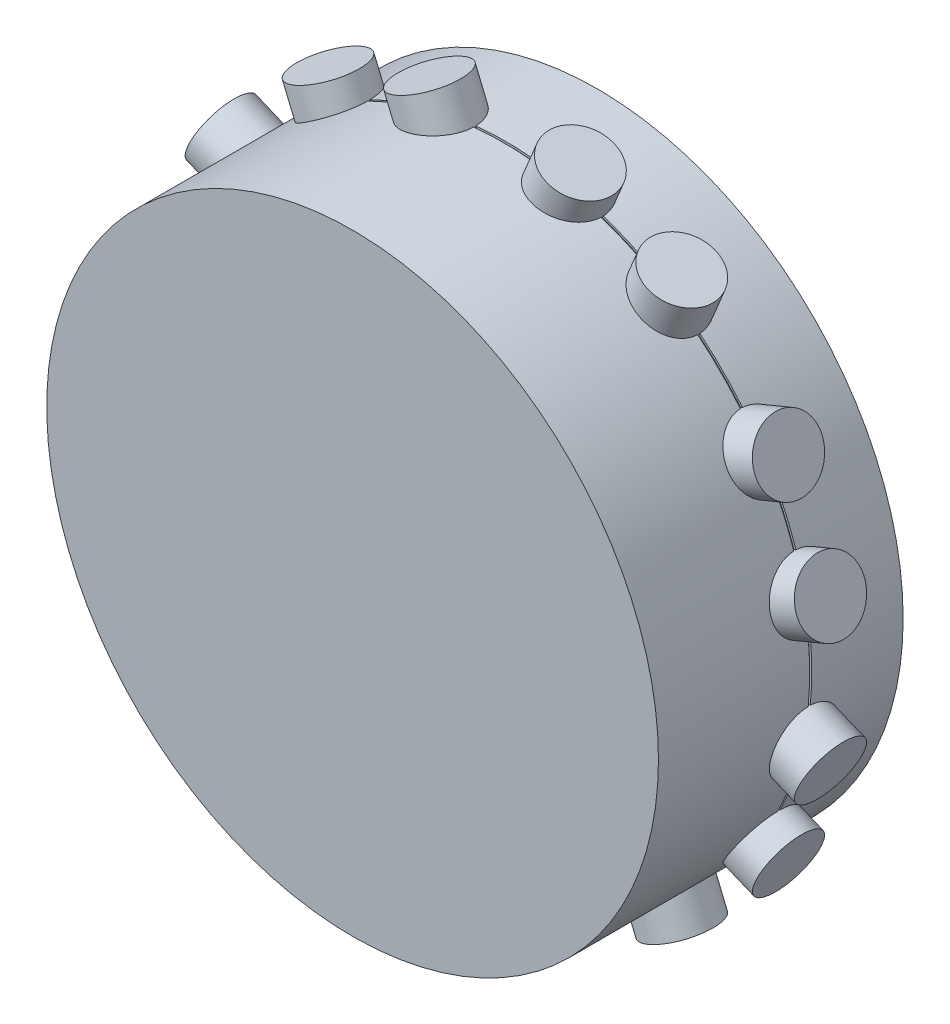
SolidWorks part; units mm, degrees
material "ABS"
ref_plane "Ebene vorne" through (0, 0, 0) normal (0, 0, 1) x (1, 0, 0)
ref_plane "Ebene oben" through (0, 0, 0) normal (0, 1, 0) x (1, 0, 0)
ref_plane "Ebene rechts" through (0, 0, 0) normal (1, 0, 0) x (0, 0, -1)
sketch "Skizze3" plane through (0, 0, 0) normal (0, 0, 1) x (1, 0, 0)
  circle A0 centre (0, 0) radius 72.5
  dimension "D1" = 145
extrude "Base" add sketch "Skizze3" along normal blind 58
sketch "Skizze6" plane through (0, 0, 0) normal (0, 1, 0) x (1, 0, 0)
  line L0 (0, 0) -> (0, -32.7476) construction
  line L1 (-72.5, 0) -> (-72.5, -58) construction
  line L2 (-72.5, -21.65) -> (-72, -21.65)
  line L3 (-72.5, -21.65) -> (-72.5, -22.15)
  line L4 (-72.5, -22.15) -> (-72, -22.15)
  line L5 (-72, -21.65) -> (-72, -22.15)
  line L6 (72.5, 0) -> (-72.5, 0) construction
  dimension "D1" = 21.65
  dimension "D2" = 0.5
  dimension "D3" = 0.5
revolve "Ring Marking" cut sketch "Skizze6" angle 360 about L0
sketch "Skizze4" plane through (0, 0, 58) normal (0, 0, 1) x (1, 0, 0)
  line L0 (0, 0) -> (66.9813, 27.7445) construction
  line L1 (0, 0) -> (72.5, 0) construction
  line L2 (61.1861, 41.7352) -> (72.7764, 13.7539)
  circle A0 centre (0, 0) radius 72.5 construction
  dimension "D1" = 22.5
ref_plane "Ebene1" through (66.9813, 27.7445, 0) normal (-0.9239, -0.3827, 0) x (0.3827, -0.9239, 0)
sketch "Skizze5" plane through (66.9813, 27.7445, 0) normal (-0.9239, -0.3827, 0) x (0.3827, -0.9239, 0)
  line L0 (0, 0) -> (0, 58) construction
  line L1 (-15.1434, 58) -> (15.1434, 58) construction
  line L2 (-72.5, 0) -> (72.5, 0) construction
  circle A0 centre (-13, 21.9) radius 8
  circle A1 centre (13, 21.9) radius 8
  dimension "D1" = 16
  dimension "D2" = 26
  dimension "D3" = 21.9
extrude "HC-SR04" add sketch "Skizze5" along normal up to body and the other way blind 5.65 separate body
pattern_circular "Kreismuster1" count 8 over 360 about axis through (0, 0, 0) along (0, 0, 1) of "HC-SR04"
